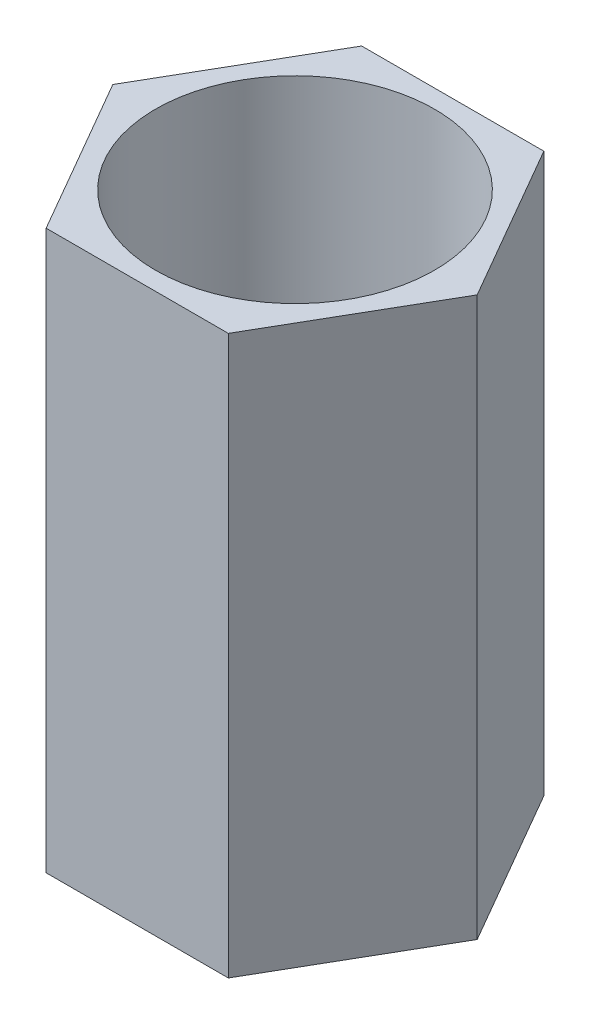
SolidWorks part; units mm, degrees
ref_plane "Front Plane" through (0, 0, 0) normal (0, 0, 1) x (1, 0, 0)
ref_plane "Top Plane" through (0, 0, 0) normal (0, 1, 0) x (1, 0, 0)
ref_plane "Right Plane" through (0, 0, 0) normal (1, 0, 0) x (0, 0, -1)
sketch "Sketch1" plane through (0, 0, 0) normal (0, 1, 0) x (1, 0, 0)
  line L1 (0.979, -1.6957) -> (1.958, 0)
  line L2 (1.958, 0) -> (0.979, 1.6957)
  line L3 (0.979, 1.6957) -> (-0.979, 1.6957)
  line L4 (-0.979, 1.6957) -> (-1.958, 0)
  line L5 (-1.958, 0) -> (-0.979, -1.6957)
  line L6 (-0.979, -1.6957) -> (0.979, -1.6957)
  circle A0 centre (0, 0) radius 1.6957 construction
  circle A1 centre (0, 0) radius 1.5
  dimension "D1" = 3
extrude "Boss-Extrude1" add sketch "Sketch1" along normal blind 6
